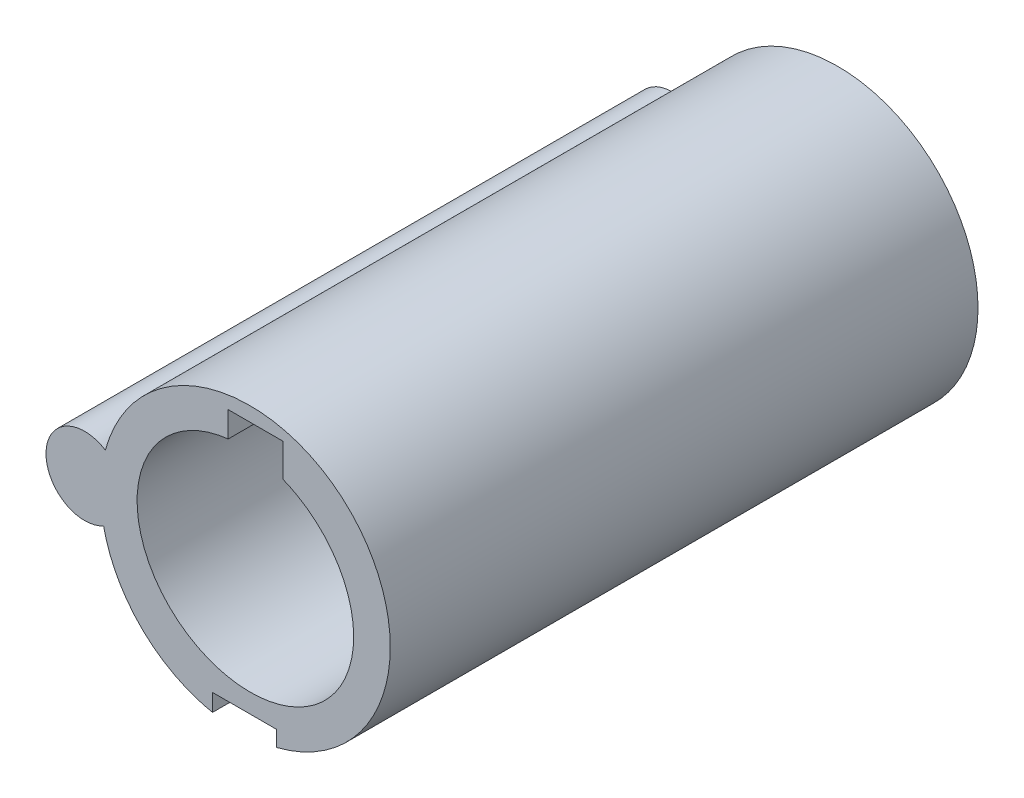
SolidWorks part; units mm, degrees
ref_plane "Plan de face" through (0, 0, 0) normal (0, 0, 1) x (1, 0, 0)
ref_plane "Plan de dessus" through (0, 0, 0) normal (0, 1, 0) x (1, 0, 0)
ref_plane "Plan de droite" through (0, 0, 0) normal (1, 0, 0) x (0, 0, -1)
sketch "Esquisse1" plane through (0, 0, 0) normal (0, 0, 1) x (1, 0, 0)
  ellipse E0 centre (0, 0) end of major axis (33.7238, 25.6943) minor radius 41.0291
  ellipse E1 centre (0, 0) end of major axis (28.4983, -13.7652) minor radius 29.8771
extrude "Boss.-Extru.1" add sketch "Esquisse1" along normal blind 170
sketch "Esquisse2" plane through (0, 0, 170) normal (0, 0, 1) x (1, 0, 0)
  line L1 (-4.9697, 37.3835) -> (10.823, 37.3835)
  line L2 (-4.9697, 37.3835) -> (-4.9697, 21.0386)
  line L3 (-4.9697, 21.0386) -> (10.823, 21.0386)
  line L4 (10.823, 37.3835) -> (10.823, 21.0386)
  line L5 (-9.4977, -35.7269) -> (9.056, -35.7269)
  line L6 (-9.4977, -35.7269) -> (-9.4977, -47.5439)
  line L7 (-9.4977, -47.5439) -> (9.056, -47.5439)
  line L8 (9.056, -35.7269) -> (9.056, -47.5439)
extrude "Enlèv. mat.-Extru.1" cut sketch "Esquisse2" against normal blind 170
sketch "Esquisse3" plane through (0, 0, 170) normal (0, 0, 1) x (1, 0, 0)
  circle A0 centre (-46.4823, 0) radius 11.1932
  point P2 (-46.4823, 0)
extrude "Boss.-Extru.2" add sketch "Esquisse3" against normal blind 170
